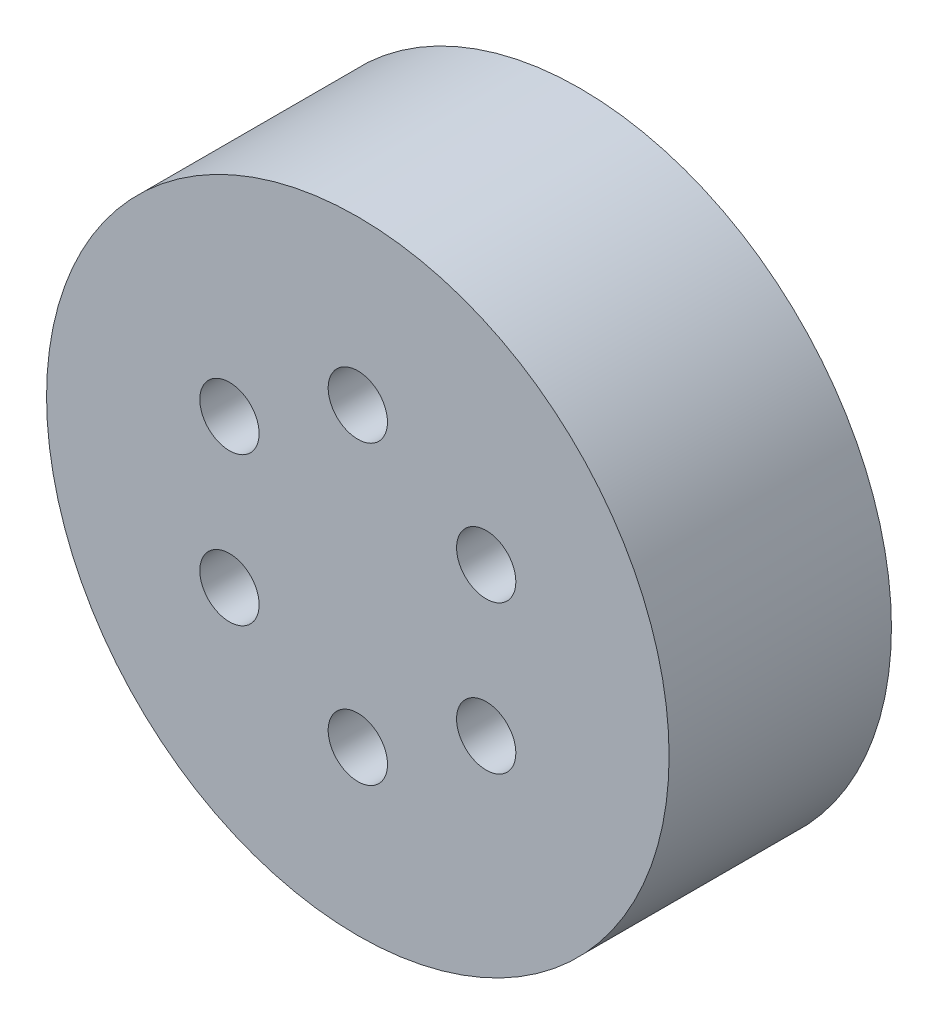
SolidWorks part; units mm, degrees
ref_plane "前视基准面" through (0, 0, 0) normal (0, 0, 1) x (1, 0, 0)
ref_plane "上视基准面" through (0, 0, 0) normal (0, 1, 0) x (1, 0, 0)
ref_plane "右视基准面" through (0, 0, 0) normal (1, 0, 0) x (0, 0, -1)
other "质心 (COM)"
sketch "草图1" plane through (0, 0, 0) normal (0, 0, 1) x (1, 0, 0)
  circle A0 centre (0, 0) radius 21
  dimension "D1" = 42
extrude "凸台-拉伸1" add sketch "草图1" along normal blind 15
sketch "草图2" plane through (0, 0, 15) normal (0, 0, 1) x (1, 0, 0)
  circle A0 centre (0, 10) radius 2
  circle A1 centre (8.6603, 5) radius 2
  circle A2 centre (8.6603, -5) radius 2
  circle A3 centre (0, -10) radius 2
  circle A4 centre (-8.6603, -5) radius 2
  circle A5 centre (-8.6603, 5) radius 2
  point P16 (0, 0)
  dimension "D1" = 10
  dimension "D2" = 4
  dimension "D3" = 6
extrude "切除-拉伸1" cut sketch "草图2" against normal through all
